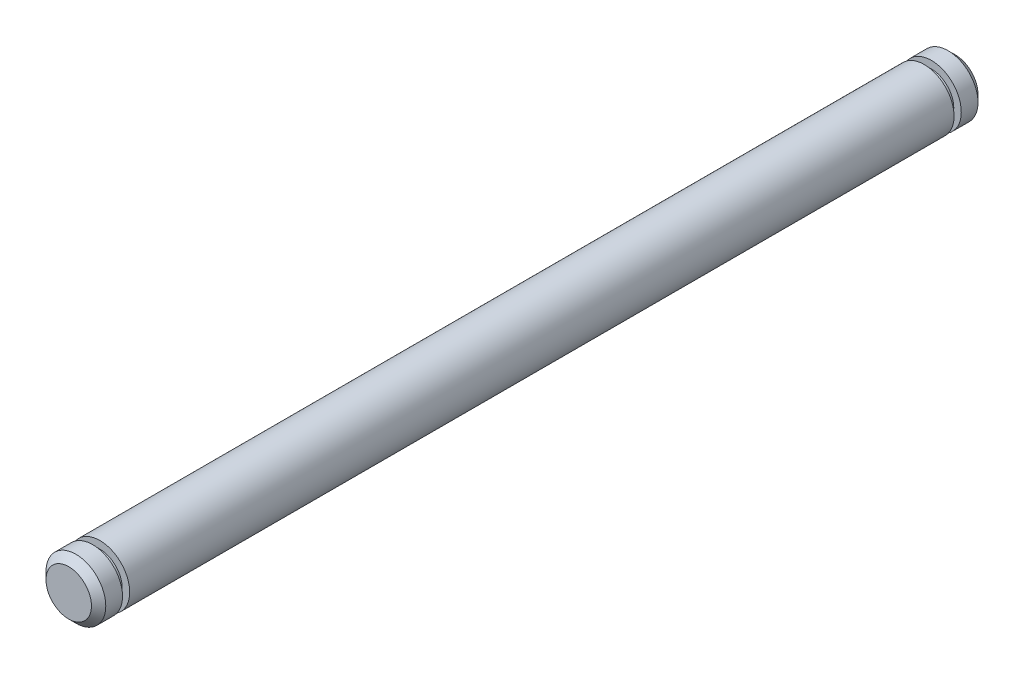
SolidWorks part; units mm, degrees
material "Alloy Steel"
ref_plane "Front Plane" through (0, 0, 0) normal (0, 0, 1) x (1, 0, 0)
ref_plane "Top Plane" through (0, 0, 0) normal (0, 1, 0) x (1, 0, 0)
ref_plane "Right Plane" through (0, 0, 0) normal (1, 0, 0) x (0, 0, -1)
sketch "Sketch1" plane through (0, 0, 0) normal (0, 0, 1) x (1, 0, 0)
  circle A0 centre (0, 0) radius 1.5875
  dimension "D1" = 3.175
extrude "Boss-Extrude1" add sketch "Sketch1" along normal mid plane 43.7845
sketch "Sketch2" plane through (0, 0, 21.8923) normal (0, 0, 1) x (1, 0, 0)
  circle A0 centre (0, 0) radius 1.1913
  dimension "D1" = 2.3825
extrude "Boss-Extrude2" add sketch "Sketch2" along normal blind 0.381
sketch "Sketch3" plane through (0, 0, 22.2733) normal (0, 0, 1) x (1, 0, 0)
  circle A0 centre (0, 0) radius 1.5875 construction
  circle A1 centre (0, 0) radius 1.5875
extrude "Boss-Extrude3" add sketch "Sketch3" along normal blind 1.27
chamfer "Chamfer1" distance 0.381 angle 45 1 edges at (1.5875, 0, 23.5433)
mirror "Mirror1" about plane through (0, 0, 0) normal (0, 0, 1) of "Boss-Extrude2", "Boss-Extrude3", "Chamfer1"
